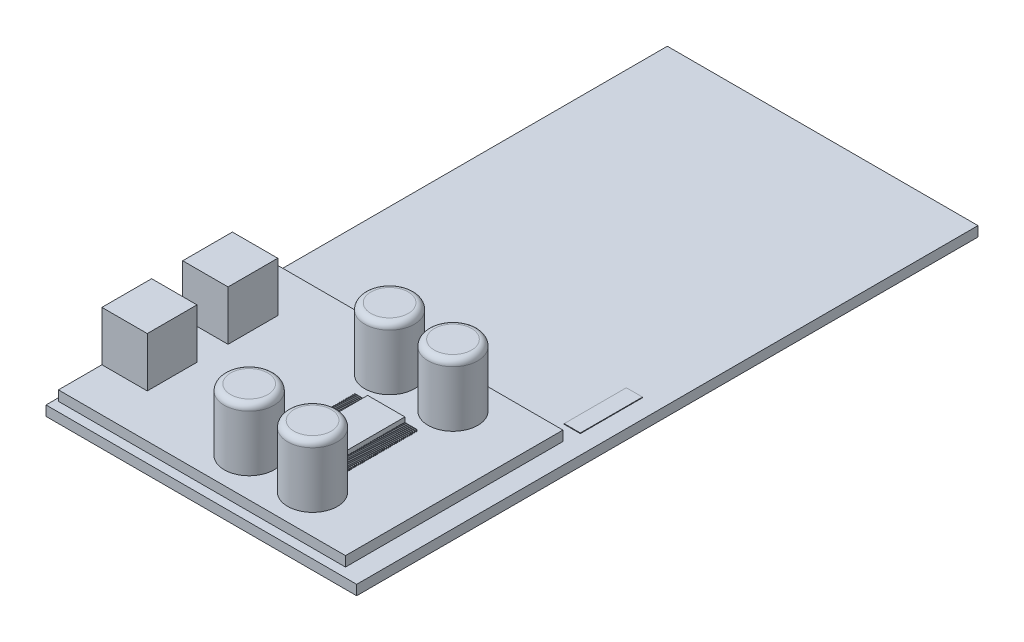
SolidWorks part; units mm, degrees
ref_plane "Front Plane" through (0, 0, 0) normal (0, 0, 1) x (1, 0, 0)
ref_plane "Top Plane" through (0, 0, 0) normal (0, 1, 0) x (1, 0, 0)
ref_plane "Right Plane" through (0, 0, 0) normal (1, 0, 0) x (0, 0, -1)
sketch "Sketch1" plane through (0, 0, 0) normal (0, 1, 0) x (1, 0, 0)
  line L5 (0, 0) -> (50, 0)
  line L6 (0, 0) -> (0, 100)
  line L7 (0, 100) -> (50, 100)
  line L8 (50, 0) -> (50, 100)
  dimension "D1" = 50
  dimension "D2" = 100
extrude "Boss-Extrude1" add sketch "Sketch1" along normal blind 1.6
sketch "Sketch2" plane through (0, 1.6, 0) normal (0, 1, 0) x (1, 0, 0)
  line L0 (50, 0) -> (50, 100) construction
  line L1 (44.4, 39) -> (47, 39)
  line L2 (44.4, 39) -> (44.4, 49)
  line L3 (44.4, 49) -> (47, 49)
  line L4 (47, 39) -> (47, 49)
  line L5 (0, 0) -> (50, 0) construction
  dimension "D1" = 10
  dimension "D2" = 2.6
  dimension "D3" = 3
  dimension "D4" = 39
sketch "Sketch5" plane through (0, 1.6, 0) normal (0, 1, 0) x (1, 0, 0)
  line L0 (0, 100) -> (0, 0) construction
  line L1 (0.5, 1.5) -> (46.7, 1.5)
  line L2 (0.5, 1.5) -> (0.5, 36.5)
  line L3 (0.5, 36.5) -> (46.7, 36.5)
  line L4 (46.7, 1.5) -> (46.7, 36.5)
  line L5 (0, 0) -> (50, 0) construction
  point P4 (0.8107, 36.601)
  dimension "D1" = 46.2
  dimension "D2" = 35
  dimension "D3" = 0.5
  dimension "D4" = 1.5
extrude "Boss-Extrude5" add sketch "Sketch5" along normal blind 1.6
sketch "Sketch6" plane through (0, 3.2, 0) normal (0, 1, 0) x (1, 0, 0)
  line L1 (0.5, 29.5) -> (7.8, 29.5)
  line L2 (0.5, 29.5) -> (0.5, 21.5)
  line L3 (0.5, 21.5) -> (7.8, 21.5)
  line L4 (7.8, 29.5) -> (7.8, 21.5)
  line L5 (0.5, 36.5) -> (0.5, 1.5) construction
  line L6 (46.7, 36.5) -> (0.5, 36.5) construction
  line L7 (0.5, 16.5) -> (7.8, 16.5)
  line L8 (0.5, 16.5) -> (0.5, 8.5)
  line L9 (0.5, 8.5) -> (7.8, 8.5)
  line L10 (7.8, 16.5) -> (7.8, 8.5)
  dimension "D1" = 7.3
  dimension "D2" = 8
  dimension "D3" = 7
  dimension "D5" = 5
  dimension "D4" = 2
extrude "Boss-Extrude6" add sketch "Sketch6" along normal blind 8
sketch "Sketch7" plane through (0, 3.2, 0) normal (0, 1, 0) x (1, 0, 0)
  line L0 (46.7, 36.5) -> (0.5, 36.5) construction
  line L1 (0.5, 1.5) -> (46.7, 1.5) construction
  line L2 (0.5, 36.5) -> (0.5, 29.5) construction
  circle A0 centre (25, 30.3) radius 4
  circle A1 centre (35.2, 30.3) radius 4
  circle A2 centre (25, 7.7) radius 4
  circle A3 centre (35.2, 7.7) radius 4
  point P10 (0, 0)
  point P11 (0, 0)
  point P12 (0, 0)
  point P13 (0, 0)
  point P14 (14.283, 7.5746)
  dimension "D1" = 8
  dimension "D3" = 2.2
  dimension "D4" = 2.2
  dimension "D2" = 2.2
  dimension "D5" = 20.5
extrude "Boss-Extrude7" add sketch "Sketch7" along normal blind 10
fillet "Fillet1" radius 1 4 edges at (35.2, 13.2, -3.7) (25, 13.2, -3.7) (35.2, 13.2, -26.3) (25, 13.2, -26.3)
sketch "Sketch8" plane through (0, 3.2, 0) normal (0, 1, 0) x (1, 0, 0)
  line L1 (27.151, 12.8366) -> (33.151, 12.8366)
  line L2 (27.151, 12.8366) -> (27.151, 24.6151)
  line L3 (27.151, 24.6151) -> (33.151, 24.6151)
  line L4 (33.151, 12.8366) -> (33.151, 24.6151)
  dimension "D1" = 6
extrude "Boss-Extrude8" add sketch "Sketch8" along normal blind 1
sketch "Sketch9" plane through (0, 3.2, 0) normal (0, 1, 0) x (1, 0, 0)
  line L0 (25.1488, 24.5395) -> (27.1488, 24.5395)
  line L1 (33.1488, 24.5395) -> (35.1488, 24.5395)
  line L2 (33.1488, 24.5395) -> (33.1488, 24.4395)
  line L3 (33.1488, 24.4395) -> (35.1488, 24.4395)
  line L4 (35.1488, 24.5395) -> (35.1488, 24.4395)
  line L5 (25.1488, 24.5395) -> (25.1488, 24.4395)
  line L6 (25.1488, 24.4395) -> (27.1488, 24.4395)
  line L7 (27.1488, 24.5395) -> (27.1488, 24.4395)
  line L8 (25.1488, 24.2395) -> (27.1488, 24.2395)
  line L9 (25.1488, 24.2395) -> (25.1488, 24.1395)
  line L10 (25.1488, 24.1395) -> (27.1488, 24.1395)
  line L11 (27.1488, 24.2395) -> (27.1488, 24.1395)
  line L12 (25.1488, 23.9395) -> (27.1488, 23.9395)
  line L13 (25.1488, 23.9395) -> (25.1488, 23.8395)
  line L14 (25.1488, 23.8395) -> (27.1488, 23.8395)
  line L15 (27.1488, 23.9395) -> (27.1488, 23.8395)
  line L16 (25.1488, 23.6395) -> (27.1488, 23.6395)
  line L17 (25.1488, 23.6395) -> (25.1488, 23.5395)
  line L18 (25.1488, 23.5395) -> (27.1488, 23.5395)
  line L19 (27.1488, 23.6395) -> (27.1488, 23.5395)
  line L20 (25.1488, 23.3395) -> (27.1488, 23.3395)
  line L21 (25.1488, 23.3395) -> (25.1488, 23.2395)
  line L22 (25.1488, 23.2395) -> (27.1488, 23.2395)
  line L23 (27.1488, 23.3395) -> (27.1488, 23.2395)
  line L24 (25.1488, 23.0395) -> (27.1488, 23.0395)
  line L25 (25.1488, 23.0395) -> (25.1488, 22.9395)
  line L26 (25.1488, 22.9395) -> (27.1488, 22.9395)
  line L27 (27.1488, 23.0395) -> (27.1488, 22.9395)
  line L28 (25.1488, 22.7395) -> (27.1488, 22.7395)
  line L29 (25.1488, 22.7395) -> (25.1488, 22.6395)
  line L30 (25.1488, 22.6395) -> (27.1488, 22.6395)
  line L31 (27.1488, 22.7395) -> (27.1488, 22.6395)
  line L32 (25.1488, 22.4395) -> (27.1488, 22.4395)
  line L33 (25.1488, 22.4395) -> (25.1488, 22.3395)
  line L34 (25.1488, 22.3395) -> (27.1488, 22.3395)
  line L35 (27.1488, 22.4395) -> (27.1488, 22.3395)
  line L36 (25.1488, 22.1395) -> (27.1488, 22.1395)
  line L37 (25.1488, 22.1395) -> (25.1488, 22.0395)
  line L38 (25.1488, 22.0395) -> (27.1488, 22.0395)
  line L39 (27.1488, 22.1395) -> (27.1488, 22.0395)
  line L40 (25.1488, 21.8395) -> (27.1488, 21.8395)
  line L41 (25.1488, 21.8395) -> (25.1488, 21.7395)
  line L42 (25.1488, 21.7395) -> (27.1488, 21.7395)
  line L43 (27.1488, 21.8395) -> (27.1488, 21.7395)
  line L44 (25.1488, 21.5395) -> (27.1488, 21.5395)
  line L45 (25.1488, 21.5395) -> (25.1488, 21.4395)
  line L46 (25.1488, 21.4395) -> (27.1488, 21.4395)
  line L47 (27.1488, 21.5395) -> (27.1488, 21.4395)
  line L48 (25.1488, 21.2395) -> (27.1488, 21.2395)
  line L49 (25.1488, 21.2395) -> (25.1488, 21.1395)
  line L50 (25.1488, 21.1395) -> (27.1488, 21.1395)
  line L51 (27.1488, 21.2395) -> (27.1488, 21.1395)
  line L52 (25.1488, 20.9395) -> (27.1488, 20.9395)
  line L53 (25.1488, 20.9395) -> (25.1488, 20.8395)
  line L54 (25.1488, 20.8395) -> (27.1488, 20.8395)
  line L55 (27.1488, 20.9395) -> (27.1488, 20.8395)
  line L56 (25.1488, 20.6395) -> (27.1488, 20.6395)
  line L57 (25.1488, 20.6395) -> (25.1488, 20.5395)
  line L58 (25.1488, 20.5395) -> (27.1488, 20.5395)
  line L59 (27.1488, 20.6395) -> (27.1488, 20.5395)
  line L60 (25.1488, 20.3395) -> (27.1488, 20.3395)
  line L61 (25.1488, 20.3395) -> (25.1488, 20.2395)
  line L62 (25.1488, 20.2395) -> (27.1488, 20.2395)
  line L63 (27.1488, 20.3395) -> (27.1488, 20.2395)
  line L64 (25.1488, 20.0395) -> (27.1488, 20.0395)
  line L65 (25.1488, 20.0395) -> (25.1488, 19.9395)
  line L66 (25.1488, 19.9395) -> (27.1488, 19.9395)
  line L67 (27.1488, 20.0395) -> (27.1488, 19.9395)
  line L68 (25.1488, 19.7395) -> (27.1488, 19.7395)
  line L69 (25.1488, 19.7395) -> (25.1488, 19.6395)
  line L70 (25.1488, 19.6395) -> (27.1488, 19.6395)
  line L71 (27.1488, 19.7395) -> (27.1488, 19.6395)
  line L72 (25.1488, 19.4395) -> (27.1488, 19.4395)
  line L73 (25.1488, 19.4395) -> (25.1488, 19.3395)
  line L74 (25.1488, 19.3395) -> (27.1488, 19.3395)
  line L75 (27.1488, 19.4395) -> (27.1488, 19.3395)
  line L76 (25.1488, 19.1395) -> (27.1488, 19.1395)
  line L77 (25.1488, 19.1395) -> (25.1488, 19.0395)
  line L78 (25.1488, 19.0395) -> (27.1488, 19.0395)
  line L79 (27.1488, 19.1395) -> (27.1488, 19.0395)
  line L80 (25.1488, 18.8395) -> (27.1488, 18.8395)
  line L81 (25.1488, 18.8395) -> (25.1488, 18.7395)
  line L82 (25.1488, 18.7395) -> (27.1488, 18.7395)
  line L83 (27.1488, 18.8395) -> (27.1488, 18.7395)
  line L84 (25.1488, 18.5395) -> (27.1488, 18.5395)
  line L85 (25.1488, 18.5395) -> (25.1488, 18.4395)
  line L86 (25.1488, 18.4395) -> (27.1488, 18.4395)
  line L87 (27.1488, 18.5395) -> (27.1488, 18.4395)
  line L88 (25.1488, 18.2395) -> (27.1488, 18.2395)
  line L89 (25.1488, 18.2395) -> (25.1488, 18.1395)
  line L90 (25.1488, 18.1395) -> (27.1488, 18.1395)
  line L91 (27.1488, 18.2395) -> (27.1488, 18.1395)
  line L92 (25.1488, 17.9395) -> (27.1488, 17.9395)
  line L93 (25.1488, 17.9395) -> (25.1488, 17.8395)
  line L94 (25.1488, 17.8395) -> (27.1488, 17.8395)
  line L95 (27.1488, 17.9395) -> (27.1488, 17.8395)
  line L96 (25.1488, 17.6395) -> (27.1488, 17.6395)
  line L97 (25.1488, 17.6395) -> (25.1488, 17.5395)
  line L98 (25.1488, 17.5395) -> (27.1488, 17.5395)
  line L99 (27.1488, 17.6395) -> (27.1488, 17.5395)
  line L100 (25.1488, 17.3395) -> (27.1488, 17.3395)
  line L101 (25.1488, 17.3395) -> (25.1488, 17.2395)
  line L102 (25.1488, 17.2395) -> (27.1488, 17.2395)
  line L103 (27.1488, 17.3395) -> (27.1488, 17.2395)
  line L104 (25.1488, 17.0395) -> (27.1488, 17.0395)
  line L105 (25.1488, 17.0395) -> (25.1488, 16.9395)
  line L106 (25.1488, 16.9395) -> (27.1488, 16.9395)
  line L107 (27.1488, 17.0395) -> (27.1488, 16.9395)
  line L108 (25.1488, 16.7395) -> (27.1488, 16.7395)
  line L109 (25.1488, 16.7395) -> (25.1488, 16.6395)
  line L110 (25.1488, 16.6395) -> (27.1488, 16.6395)
  line L111 (27.1488, 16.7395) -> (27.1488, 16.6395)
  line L112 (25.1488, 16.4395) -> (27.1488, 16.4395)
  line L113 (25.1488, 16.4395) -> (25.1488, 16.3395)
  line L114 (25.1488, 16.3395) -> (27.1488, 16.3395)
  line L115 (27.1488, 16.4395) -> (27.1488, 16.3395)
  line L116 (25.1488, 16.1395) -> (27.1488, 16.1395)
  line L117 (25.1488, 16.1395) -> (25.1488, 16.0395)
  line L118 (25.1488, 16.0395) -> (27.1488, 16.0395)
  line L119 (27.1488, 16.1395) -> (27.1488, 16.0395)
  line L120 (25.1488, 15.8395) -> (27.1488, 15.8395)
  line L121 (25.1488, 15.8395) -> (25.1488, 15.7395)
  line L122 (25.1488, 15.7395) -> (27.1488, 15.7395)
  line L123 (27.1488, 15.8395) -> (27.1488, 15.7395)
  line L124 (25.1488, 15.5395) -> (27.1488, 15.5395)
  line L125 (25.1488, 15.5395) -> (25.1488, 15.4395)
  line L126 (25.1488, 15.4395) -> (27.1488, 15.4395)
  line L127 (27.1488, 15.5395) -> (27.1488, 15.4395)
  line L128 (25.1488, 15.2395) -> (27.1488, 15.2395)
  line L129 (25.1488, 15.2395) -> (25.1488, 15.1395)
  line L130 (25.1488, 15.1395) -> (27.1488, 15.1395)
  line L131 (27.1488, 15.2395) -> (27.1488, 15.1395)
  line L132 (25.1488, 14.9395) -> (27.1488, 14.9395)
  line L133 (25.1488, 14.9395) -> (25.1488, 14.8395)
  line L134 (25.1488, 14.8395) -> (27.1488, 14.8395)
  line L135 (27.1488, 14.9395) -> (27.1488, 14.8395)
  line L136 (25.1488, 14.6395) -> (27.1488, 14.6395)
  line L137 (25.1488, 14.6395) -> (25.1488, 14.5395)
  line L138 (25.1488, 14.5395) -> (27.1488, 14.5395)
  line L139 (27.1488, 14.6395) -> (27.1488, 14.5395)
  line L140 (25.1488, 14.3395) -> (27.1488, 14.3395)
  line L141 (25.1488, 14.3395) -> (25.1488, 14.2395)
  line L142 (25.1488, 14.2395) -> (27.1488, 14.2395)
  line L143 (27.1488, 14.3395) -> (27.1488, 14.2395)
  line L144 (25.1488, 14.0395) -> (27.1488, 14.0395)
  line L145 (25.1488, 14.0395) -> (25.1488, 13.9395)
  line L146 (25.1488, 13.9395) -> (27.1488, 13.9395)
  line L147 (27.1488, 14.0395) -> (27.1488, 13.9395)
  line L148 (25.1488, 13.7395) -> (27.1488, 13.7395)
  line L149 (25.1488, 13.7395) -> (25.1488, 13.6395)
  line L150 (25.1488, 13.6395) -> (27.1488, 13.6395)
  line L151 (27.1488, 13.7395) -> (27.1488, 13.6395)
  line L152 (25.1488, 13.4395) -> (27.1488, 13.4395)
  line L153 (25.1488, 13.4395) -> (25.1488, 13.3395)
  line L154 (25.1488, 13.3395) -> (27.1488, 13.3395)
  line L155 (27.1488, 13.4395) -> (27.1488, 13.3395)
  line L156 (25.1488, 13.1395) -> (27.1488, 13.1395)
  line L157 (25.1488, 13.1395) -> (25.1488, 13.0395)
  line L158 (25.1488, 13.0395) -> (27.1488, 13.0395)
  line L159 (27.1488, 13.1395) -> (27.1488, 13.0395)
  line L160 (33.1488, 24.2395) -> (35.1488, 24.2395)
  line L161 (33.1488, 24.2395) -> (33.1488, 24.1395)
  line L162 (33.1488, 24.1395) -> (35.1488, 24.1395)
  line L163 (35.1488, 24.2395) -> (35.1488, 24.1395)
  line L164 (33.1488, 23.9395) -> (35.1488, 23.9395)
  line L165 (33.1488, 23.9395) -> (33.1488, 23.8395)
  line L166 (33.1488, 23.8395) -> (35.1488, 23.8395)
  line L167 (35.1488, 23.9395) -> (35.1488, 23.8395)
  line L168 (33.1488, 23.6395) -> (35.1488, 23.6395)
  line L169 (33.1488, 23.6395) -> (33.1488, 23.5395)
  line L170 (33.1488, 23.5395) -> (35.1488, 23.5395)
  line L171 (35.1488, 23.6395) -> (35.1488, 23.5395)
  line L172 (33.1488, 23.3395) -> (35.1488, 23.3395)
  line L173 (33.1488, 23.3395) -> (33.1488, 23.2395)
  line L174 (33.1488, 23.2395) -> (35.1488, 23.2395)
  line L175 (35.1488, 23.3395) -> (35.1488, 23.2395)
  line L176 (33.1488, 23.0395) -> (35.1488, 23.0395)
  line L177 (33.1488, 23.0395) -> (33.1488, 22.9395)
  line L178 (33.1488, 22.9395) -> (35.1488, 22.9395)
  line L179 (35.1488, 23.0395) -> (35.1488, 22.9395)
  line L180 (33.1488, 22.7395) -> (35.1488, 22.7395)
  line L181 (33.1488, 22.7395) -> (33.1488, 22.6395)
  line L182 (33.1488, 22.6395) -> (35.1488, 22.6395)
  line L183 (35.1488, 22.7395) -> (35.1488, 22.6395)
  line L184 (33.1488, 22.4395) -> (35.1488, 22.4395)
  line L185 (33.1488, 22.4395) -> (33.1488, 22.3395)
  line L186 (33.1488, 22.3395) -> (35.1488, 22.3395)
  line L187 (35.1488, 22.4395) -> (35.1488, 22.3395)
  line L188 (33.1488, 22.1395) -> (35.1488, 22.1395)
  line L189 (33.1488, 22.1395) -> (33.1488, 22.0395)
  line L190 (33.1488, 22.0395) -> (35.1488, 22.0395)
  line L191 (35.1488, 22.1395) -> (35.1488, 22.0395)
  line L192 (33.1488, 21.8395) -> (35.1488, 21.8395)
  line L193 (33.1488, 21.8395) -> (33.1488, 21.7395)
  line L194 (33.1488, 21.7395) -> (35.1488, 21.7395)
  line L195 (35.1488, 21.8395) -> (35.1488, 21.7395)
  line L196 (33.1488, 21.5395) -> (35.1488, 21.5395)
  line L197 (33.1488, 21.5395) -> (33.1488, 21.4395)
  line L198 (33.1488, 21.4395) -> (35.1488, 21.4395)
  line L199 (35.1488, 21.5395) -> (35.1488, 21.4395)
  line L200 (33.1488, 21.2395) -> (35.1488, 21.2395)
  line L201 (33.1488, 21.2395) -> (33.1488, 21.1395)
  line L202 (33.1488, 21.1395) -> (35.1488, 21.1395)
  line L203 (35.1488, 21.2395) -> (35.1488, 21.1395)
  line L204 (33.1488, 20.9395) -> (35.1488, 20.9395)
  line L205 (33.1488, 20.9395) -> (33.1488, 20.8395)
  line L206 (33.1488, 20.8395) -> (35.1488, 20.8395)
  line L207 (35.1488, 20.9395) -> (35.1488, 20.8395)
  line L208 (33.1488, 20.6395) -> (35.1488, 20.6395)
  line L209 (33.1488, 20.6395) -> (33.1488, 20.5395)
  line L210 (33.1488, 20.5395) -> (35.1488, 20.5395)
  line L211 (35.1488, 20.6395) -> (35.1488, 20.5395)
  line L212 (33.1488, 20.3395) -> (35.1488, 20.3395)
  line L213 (33.1488, 20.3395) -> (33.1488, 20.2395)
  line L214 (33.1488, 20.2395) -> (35.1488, 20.2395)
  line L215 (35.1488, 20.3395) -> (35.1488, 20.2395)
  line L216 (33.1488, 20.0395) -> (35.1488, 20.0395)
  line L217 (33.1488, 20.0395) -> (33.1488, 19.9395)
  line L218 (33.1488, 19.9395) -> (35.1488, 19.9395)
  line L219 (35.1488, 20.0395) -> (35.1488, 19.9395)
  line L220 (33.1488, 19.7395) -> (35.1488, 19.7395)
  line L221 (33.1488, 19.7395) -> (33.1488, 19.6395)
  line L222 (33.1488, 19.6395) -> (35.1488, 19.6395)
  line L223 (35.1488, 19.7395) -> (35.1488, 19.6395)
  line L224 (33.1488, 19.4395) -> (35.1488, 19.4395)
  line L225 (33.1488, 19.4395) -> (33.1488, 19.3395)
  line L226 (33.1488, 19.3395) -> (35.1488, 19.3395)
  line L227 (35.1488, 19.4395) -> (35.1488, 19.3395)
  line L228 (33.1488, 19.1395) -> (35.1488, 19.1395)
  line L229 (33.1488, 19.1395) -> (33.1488, 19.0395)
  line L230 (33.1488, 19.0395) -> (35.1488, 19.0395)
  line L231 (35.1488, 19.1395) -> (35.1488, 19.0395)
  line L232 (33.1488, 18.8395) -> (35.1488, 18.8395)
  line L233 (33.1488, 18.8395) -> (33.1488, 18.7395)
  line L234 (33.1488, 18.7395) -> (35.1488, 18.7395)
  line L235 (35.1488, 18.8395) -> (35.1488, 18.7395)
  line L236 (33.1488, 18.5395) -> (35.1488, 18.5395)
  line L237 (33.1488, 18.5395) -> (33.1488, 18.4395)
  line L238 (33.1488, 18.4395) -> (35.1488, 18.4395)
  line L239 (35.1488, 18.5395) -> (35.1488, 18.4395)
  line L240 (33.1488, 18.2395) -> (35.1488, 18.2395)
  line L241 (33.1488, 18.2395) -> (33.1488, 18.1395)
  line L242 (33.1488, 18.1395) -> (35.1488, 18.1395)
  line L243 (35.1488, 18.2395) -> (35.1488, 18.1395)
  line L244 (33.1488, 17.9395) -> (35.1488, 17.9395)
  line L245 (33.1488, 17.9395) -> (33.1488, 17.8395)
  line L246 (33.1488, 17.8395) -> (35.1488, 17.8395)
  line L247 (35.1488, 17.9395) -> (35.1488, 17.8395)
  line L248 (33.1488, 17.6395) -> (35.1488, 17.6395)
  line L249 (33.1488, 17.6395) -> (33.1488, 17.5395)
  line L250 (33.1488, 17.5395) -> (35.1488, 17.5395)
  line L251 (35.1488, 17.6395) -> (35.1488, 17.5395)
  line L252 (33.1488, 17.3395) -> (35.1488, 17.3395)
  line L253 (33.1488, 17.3395) -> (33.1488, 17.2395)
  line L254 (33.1488, 17.2395) -> (35.1488, 17.2395)
  line L255 (35.1488, 17.3395) -> (35.1488, 17.2395)
  line L256 (33.1488, 17.0395) -> (35.1488, 17.0395)
  line L257 (33.1488, 17.0395) -> (33.1488, 16.9395)
  line L258 (33.1488, 16.9395) -> (35.1488, 16.9395)
  line L259 (35.1488, 17.0395) -> (35.1488, 16.9395)
  line L260 (33.1488, 16.7395) -> (35.1488, 16.7395)
  line L261 (33.1488, 16.7395) -> (33.1488, 16.6395)
  line L262 (33.1488, 16.6395) -> (35.1488, 16.6395)
  line L263 (35.1488, 16.7395) -> (35.1488, 16.6395)
  line L264 (33.1488, 16.4395) -> (35.1488, 16.4395)
  line L265 (33.1488, 16.4395) -> (33.1488, 16.3395)
  line L266 (33.1488, 16.3395) -> (35.1488, 16.3395)
  line L267 (35.1488, 16.4395) -> (35.1488, 16.3395)
  line L268 (33.1488, 16.1395) -> (35.1488, 16.1395)
  line L269 (33.1488, 16.1395) -> (33.1488, 16.0395)
  line L270 (33.1488, 16.0395) -> (35.1488, 16.0395)
  line L271 (35.1488, 16.1395) -> (35.1488, 16.0395)
  line L272 (33.1488, 15.8395) -> (35.1488, 15.8395)
  line L273 (33.1488, 15.8395) -> (33.1488, 15.7395)
  line L274 (33.1488, 15.7395) -> (35.1488, 15.7395)
  line L275 (35.1488, 15.8395) -> (35.1488, 15.7395)
  line L276 (33.1488, 15.5395) -> (35.1488, 15.5395)
  line L277 (33.1488, 15.5395) -> (33.1488, 15.4395)
  line L278 (33.1488, 15.4395) -> (35.1488, 15.4395)
  line L279 (35.1488, 15.5395) -> (35.1488, 15.4395)
  line L280 (33.1488, 15.2395) -> (35.1488, 15.2395)
  line L281 (33.1488, 15.2395) -> (33.1488, 15.1395)
  line L282 (33.1488, 15.1395) -> (35.1488, 15.1395)
  line L283 (35.1488, 15.2395) -> (35.1488, 15.1395)
  line L284 (33.1488, 14.9395) -> (35.1488, 14.9395)
  line L285 (33.1488, 14.9395) -> (33.1488, 14.8395)
  line L286 (33.1488, 14.8395) -> (35.1488, 14.8395)
  line L287 (35.1488, 14.9395) -> (35.1488, 14.8395)
  line L288 (33.1488, 14.6395) -> (35.1488, 14.6395)
  line L289 (33.1488, 14.6395) -> (33.1488, 14.5395)
  line L290 (33.1488, 14.5395) -> (35.1488, 14.5395)
  line L291 (35.1488, 14.6395) -> (35.1488, 14.5395)
  line L292 (33.1488, 14.3395) -> (35.1488, 14.3395)
  line L293 (33.1488, 14.3395) -> (33.1488, 14.2395)
  line L294 (33.1488, 14.2395) -> (35.1488, 14.2395)
  line L295 (35.1488, 14.3395) -> (35.1488, 14.2395)
  line L296 (33.1488, 14.0395) -> (35.1488, 14.0395)
  line L297 (33.1488, 14.0395) -> (33.1488, 13.9395)
  line L298 (33.1488, 13.9395) -> (35.1488, 13.9395)
  line L299 (35.1488, 14.0395) -> (35.1488, 13.9395)
  line L300 (33.1488, 13.7395) -> (35.1488, 13.7395)
  line L301 (33.1488, 13.7395) -> (33.1488, 13.6395)
  line L302 (33.1488, 13.6395) -> (35.1488, 13.6395)
  line L303 (35.1488, 13.7395) -> (35.1488, 13.6395)
  line L304 (33.1488, 13.4395) -> (35.1488, 13.4395)
  line L305 (33.1488, 13.4395) -> (33.1488, 13.3395)
  line L306 (33.1488, 13.3395) -> (35.1488, 13.3395)
  line L307 (35.1488, 13.4395) -> (35.1488, 13.3395)
  line L308 (33.1488, 13.1395) -> (35.1488, 13.1395)
  line L309 (33.1488, 13.1395) -> (33.1488, 13.0395)
  line L310 (33.1488, 13.0395) -> (35.1488, 13.0395)
  line L311 (35.1488, 13.1395) -> (35.1488, 13.0395)
  dimension "D1" = 2
  dimension "D2" = 0.1
extrude "Boss-Extrude9" add sketch "Sketch9" along normal blind 0.3
extrude "Boss-Extrude11" add sketch "Sketch2" along normal blind 0.1
sketch "Sketch15" plane through (0, 0, 0) normal (0, -1, 0) x (1, 0, 0)
  line L1 (32.1, -100) -> (0.5, -100)
  line L2 (32.1, -100) -> (32.1, -83)
  line L3 (32.1, -83) -> (0.5, -83)
  line L4 (0.5, -100) -> (0.5, -83)
  line L5 (50, -100) -> (0, -100) construction
  line L6 (0, -100) -> (0, 0) construction
  dimension "D1" = 31.6
  dimension "D2" = 17
  dimension "D3" = 0.5
extrude "Boss-Extrude12" add sketch "Sketch15" along normal blind 1.6
